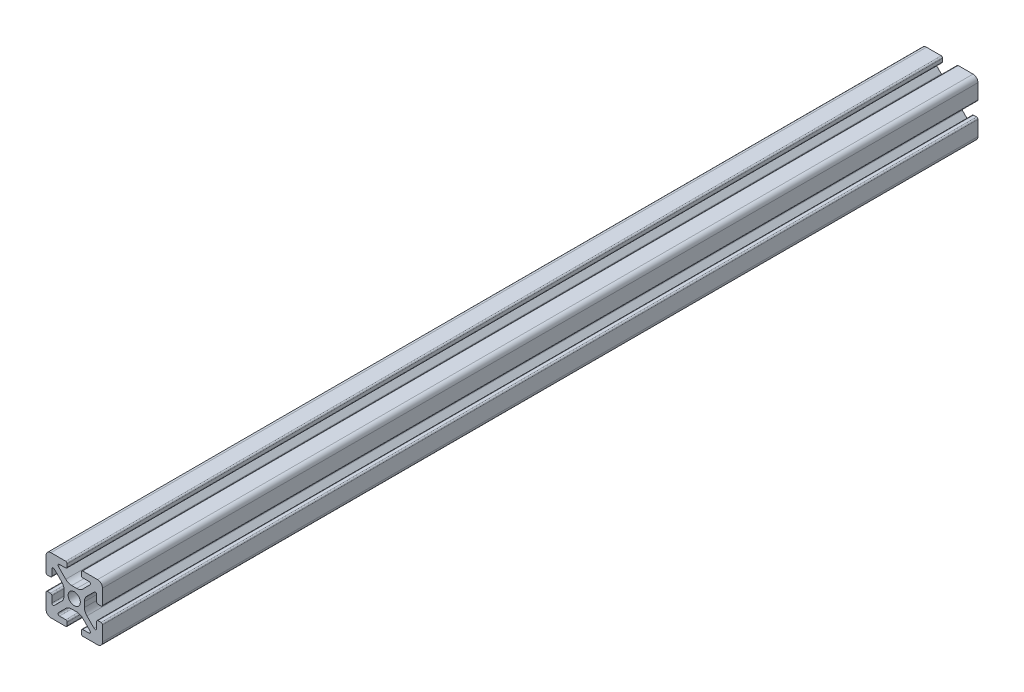
SolidWorks part; units mm, degrees
ref_plane "Front Plane" through (0, 0, 0) normal (0, 0, 1) x (1, 0, 0)
ref_plane "Top Plane" through (0, 0, 0) normal (0, 1, 0) x (1, 0, 0)
ref_plane "Right Plane" through (0, 0, 0) normal (1, 0, 0) x (0, 0, -1)
sketch "Sketch2" plane through (0, 0, 0) normal (0, 0, 1) x (1, 0, 0)
  line L0 (0, 10) -> (0, -10) construction
  line L1 (-10, 0) -> (10, 0) construction
  line L2 (2.5, -10) -> (10, -10)
  line L3 (10, -10) -> (10, -2.5)
  line L4 (2.5, -10) -> (2.5, -7.9246)
  line L5 (2.5, -7.9246) -> (6.4571, -7.9246)
  line L6 (6.4571, -7.9246) -> (2.1325, -3.6)
  line L7 (0, 0) -> (10, -10) construction
  line L8 (10, -2.5) -> (7.9246, -2.5)
  line L9 (7.9246, -2.5) -> (7.9246, -6.4571)
  line L10 (7.9246, -6.4571) -> (3.6, -2.1325)
  line L11 (5.7623, -4.2948) -> (4.2948, -5.7623) construction
  circle A0 centre (0, 0) radius 2.15
  arc A1 (5.25, -7.9246) -> (5.6036, -7.0711) centre (5.25, -7.4246) ccw construction
  point P8 (0, -3.6)
  point P16 (5.0286, -5.0286)
  dimension "Center Hole Diameter" = 4.3
  dimension "D3" = 0.5
  dimension "Rail Height" = 20
  dimension "Rail Width" = 20
  dimension "T-Slot Width" = 5
  dimension "Slot Depth" = 6.4
  dimension "Slot Inner Width" = 11.5
sketch "Sketch3" plane through (0, 0, 0) normal (1, 0, 0) x (0, 0, -1)
  line L0 (-76.2, -10) -> (76.2, -10) construction
  line L1 (-50.8, 0) -> (50.8, 0) construction
  line L2 (0, 10) -> (0, -10) construction
  line L3 (0, 10) -> (0, -10) construction
  point P6 (-50.8, 0)
  point P8 (50.8, 0)
  dimension "D1" = 25.4
  dimension "Length" = 152.4
sketch "Sketch4" plane through (0, 0, 0) normal (0, 0, 1) x (1, 0, 0)
  line L0 (3, -10) -> (8.25, -10)
  line L1 (2.5, -10) -> (10, -10) construction
  line L2 (2.5, -10) -> (2.5, -7.9246) construction
  line L3 (2.5, -7.9246) -> (6.4571, -7.9246) construction
  line L4 (2.5, -8.4246) -> (2.5, -9.5)
  line L5 (3, -7.9246) -> (5.25, -7.9246)
  line L6 (0, -3.6) -> (0.8898, -3.6)
  line L7 (6.4571, -7.9246) -> (2.1325, -3.6) construction
  line L8 (3.0112, -4.4787) -> (5.6036, -7.0711)
  line L9 (10, -10) -> (10, -2.5) construction
  line L10 (7.9246, -6.4571) -> (3.6, -2.1325) construction
  line L11 (7.9246, -2.5) -> (7.9246, -6.4571) construction
  line L12 (7.9246, -5.25) -> (7.9246, -3)
  line L13 (10, -2.5) -> (7.9246, -2.5) construction
  line L14 (8.4246, -2.5) -> (9.5, -2.5)
  line L15 (10, -3) -> (10, -8.25)
  line L16 (7.0711, -5.6036) -> (4.4787, -3.0112)
  line L17 (3.6, 0) -> (3.6, -0.8898)
  line L18 (-10, 0) -> (10, 0) construction
  line L19 (0, -3.6) -> (0, -2.15)
  line L20 (0, 10) -> (0, -10) construction
  line L21 (3.6, 0) -> (2.15, 0)
  arc A0 (2.5, -9.5) -> (3, -10) centre (3, -9.5) ccw
  arc A1 (5.25, -7.9246) -> (5.6036, -7.0711) centre (5.25, -7.4246) ccw construction
  arc A2 (2.5, -8.4246) -> (3, -7.9246) centre (3, -8.4246) cw
  arc A3 (5.25, -7.9246) -> (5.6036, -7.0711) centre (5.25, -7.4246) ccw
  arc A4 (0.8898, -3.6) -> (3.0112, -4.4787) centre (0.8898, -6.6) cw
  arc A5 (8.25, -10) -> (10, -8.25) centre (8.25, -8.25) ccw
  arc A6 (7.0711, -5.6036) -> (7.9246, -5.25) centre (7.4246, -5.25) ccw
  arc A7 (7.9246, -3) -> (8.4246, -2.5) centre (8.4246, -3) cw
  arc A8 (9.5, -2.5) -> (10, -3) centre (9.5, -3) cw
  arc A9 (4.4787, -3.0112) -> (3.6, -0.8898) centre (6.6, -0.8898) cw
  circle A10 centre (0, 0) radius 2.15 construction
  arc A11 (0, -2.15) -> (2.15, 0) centre (0, 0) ccw
  dimension "D1" = 1.75
  dimension "D2" = 3
extrude "Boss-Extrude1" add sketch "Sketch4" along normal mid plane 310
mirror "Mirror1" about plane through (0, 0, 0) normal (1, 0, 0) of bodies 134
mirror "Mirror2" about plane through (0, 0, 0) normal (0, 1, 0) of bodies 135
equation "\"D3@Sketch2\"=\"T-Slot Width@Sketch2\"*0.1"
equation "\"D1@Sketch4\"=\"D3@Sketch2\"*3.5"
equation "\"D2@Sketch4\"=\"D3@Sketch2\"*6"
equation "\"D1@Boss-Extrude1\"=110"
